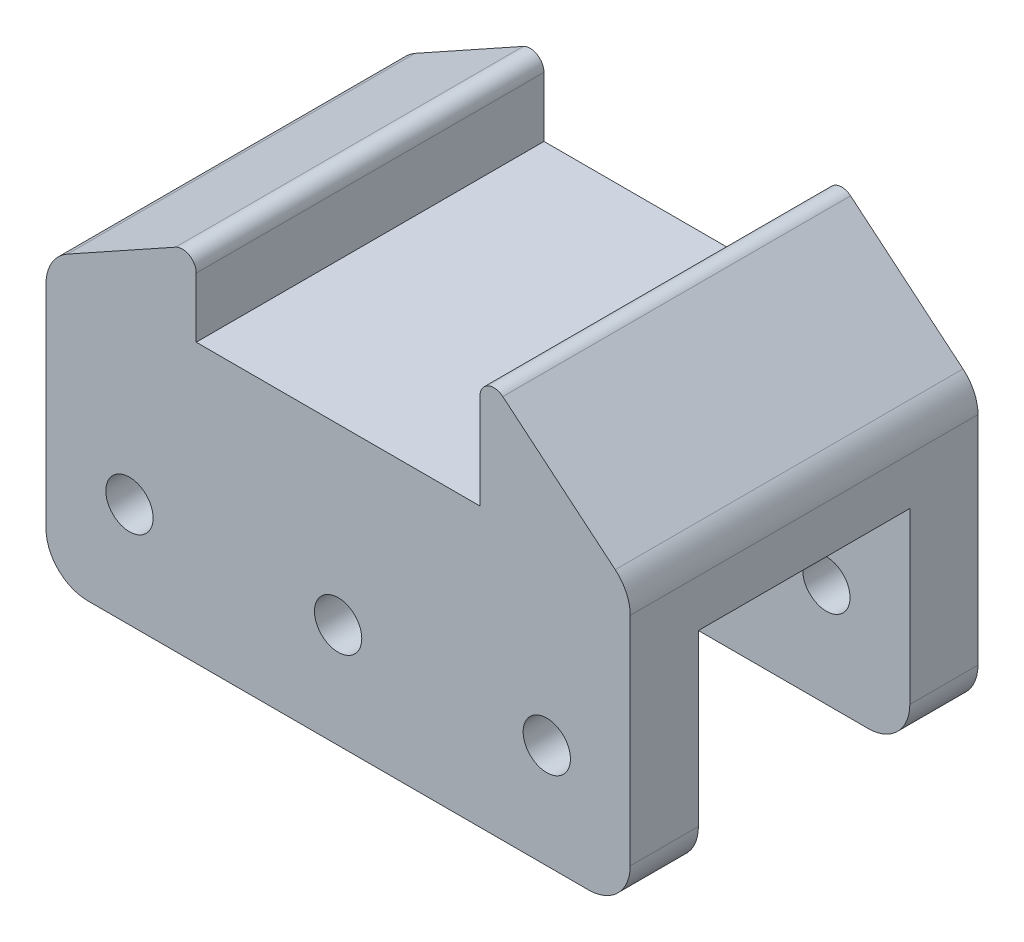
SolidWorks part; units mm, degrees
ref_plane "前视基准面" through (0, 0, 0) normal (0, 0, 1) x (1, 0, 0)
ref_plane "上视基准面" through (0, 0, 0) normal (0, 1, 0) x (1, 0, 0)
ref_plane "右视基准面" through (0, 0, 0) normal (1, 0, 0) x (0, 0, -1)
sketch "草图1" plane through (0, 0, 0) normal (0, 1, 0) x (1, 0, 0)
  line L1 (0, 0) -> (42, 0)
  line L2 (0, 0) -> (0, 25)
  line L3 (0, 25) -> (42, 25)
  line L4 (42, 0) -> (42, 25)
  dimension "D1" = 42
  dimension "D2" = 25
extrude "凸台-拉伸1" add sketch "草图1" along normal blind 20
sketch "草图2" plane through (0, 0, 0) normal (-1, 0, 0) x (0, 0, 1)
  line L0 (-25, 0) -> (0, 0) construction
  line L1 (-20.1, 0) -> (-4.9, 0)
  line L2 (-20.1, 0) -> (-20.1, 15.2)
  line L3 (-20.1, 15.2) -> (-4.9, 15.2)
  line L4 (-4.9, 0) -> (-4.9, 15.2)
  point P6 (-12.5, 0)
  point P7 (-14.1717, 0)
  dimension "D1" = 15.2
extrude "切除-拉伸1" cut sketch "草图2" against normal through all
sketch "草图4" plane through (0, 0, 0) normal (0, 0, 1) x (1, 0, 0)
  line L1 (10.8, 26) -> (10.8, 20)
  line L2 (0, 20) -> (42, 20) construction
  line L3 (31.2, 20) -> (31.2, 29)
  line L4 (31.2, 29) -> (42, 20)
  line L7 (0, 20) -> (10.8, 26)
  line L8 (10.8, 20) -> (0, 20)
  line L9 (31.2, 20) -> (42, 20)
  point P8 (-0.7054, 20)
  point P12 (60, 20.7129)
  dimension "D2" = 6
  dimension "D3" = 9
  dimension "D4" = 20.4
extrude "凸台-拉伸2" add sketch "草图4" against normal up to surface (25 mm away) up to face at (21, 10, -25)
sketch "草图5" plane through (0, 0, 0) normal (0, 0, 1) x (1, 0, 0)
  line L0 (0, 7.5) -> (6, 7.5) construction
  line L1 (0, 20) -> (0, 0) construction
  line L2 (6, 7.5) -> (21, 7.5) construction
  line L3 (21, 7.5) -> (36, 7.5) construction
  line L4 (36, 7.5) -> (42, 7.5) construction
  line L5 (42, 20) -> (42, 0) construction
  line L6 (0, 0) -> (42, 0) construction
  circle A0 centre (6, 7.5) radius 1.7
  circle A1 centre (21, 7.5) radius 1.7
  circle A2 centre (36, 7.5) radius 1.7
  dimension "D3" = 3.4
  dimension "D1" = 6
  dimension "D2" = 7.5
extrude "切除-拉伸2" cut sketch "草图5" against normal through all
fillet "圆角1" radius 3 6 edges at (42, 0, -22.55) (42, 0, -2.45) (0, 0, -22.55) (0, 0, -2.45) (42, 20, -12.5) (0, 20, -12.5)
fillet "圆角3" radius 1 2 edges at (10.8, 26, -12.5) (31.2, 29, -12.5)
